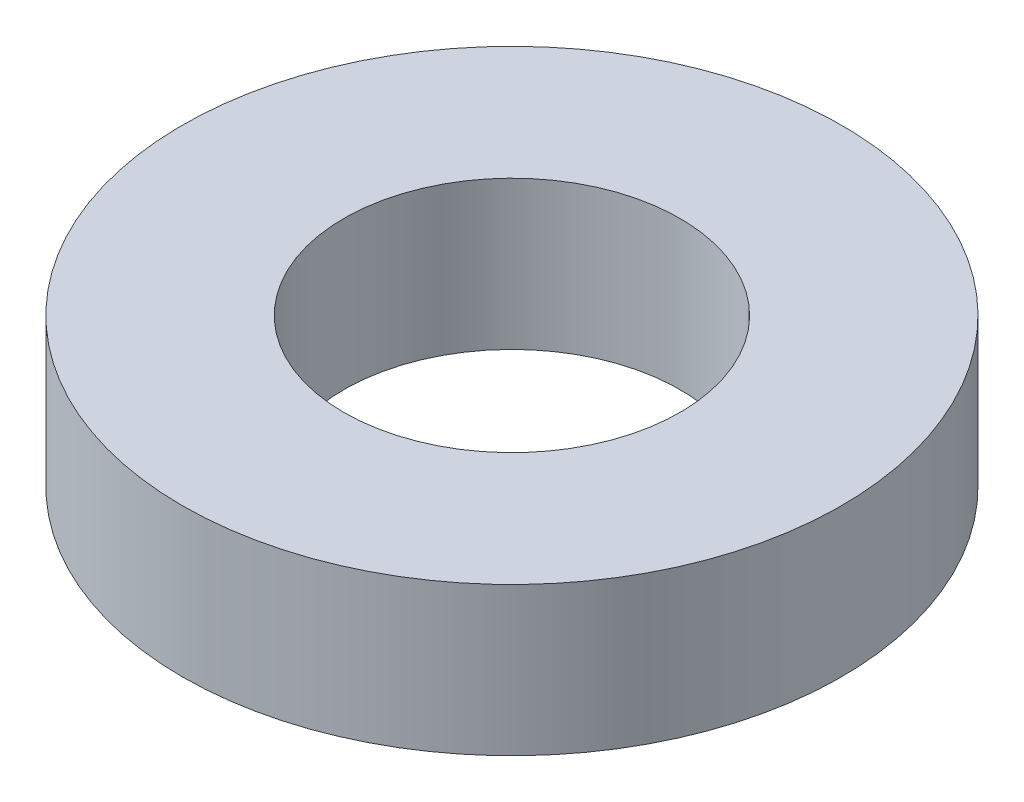
SolidWorks part; units mm, degrees
ref_plane "前视基准面" through (0, 0, 0) normal (0, 0, 1) x (1, 0, 0)
ref_plane "上视基准面" through (0, 0, 0) normal (0, 1, 0) x (1, 0, 0)
ref_plane "右视基准面" through (0, 0, 0) normal (1, 0, 0) x (0, 0, -1)
other "Configuration Table"
sketch "草图1" plane through (0, 0, 0) normal (0, 1, 0) x (1, 0, 0)
  circle A0 centre (0, 0) radius 2.55
  circle A1 centre (0, 0) radius 5
  dimension "D1" = 5.1
  dimension "D2" = 10
extrude "凸台-拉伸1" add sketch "草图1" along normal blind 2.25
